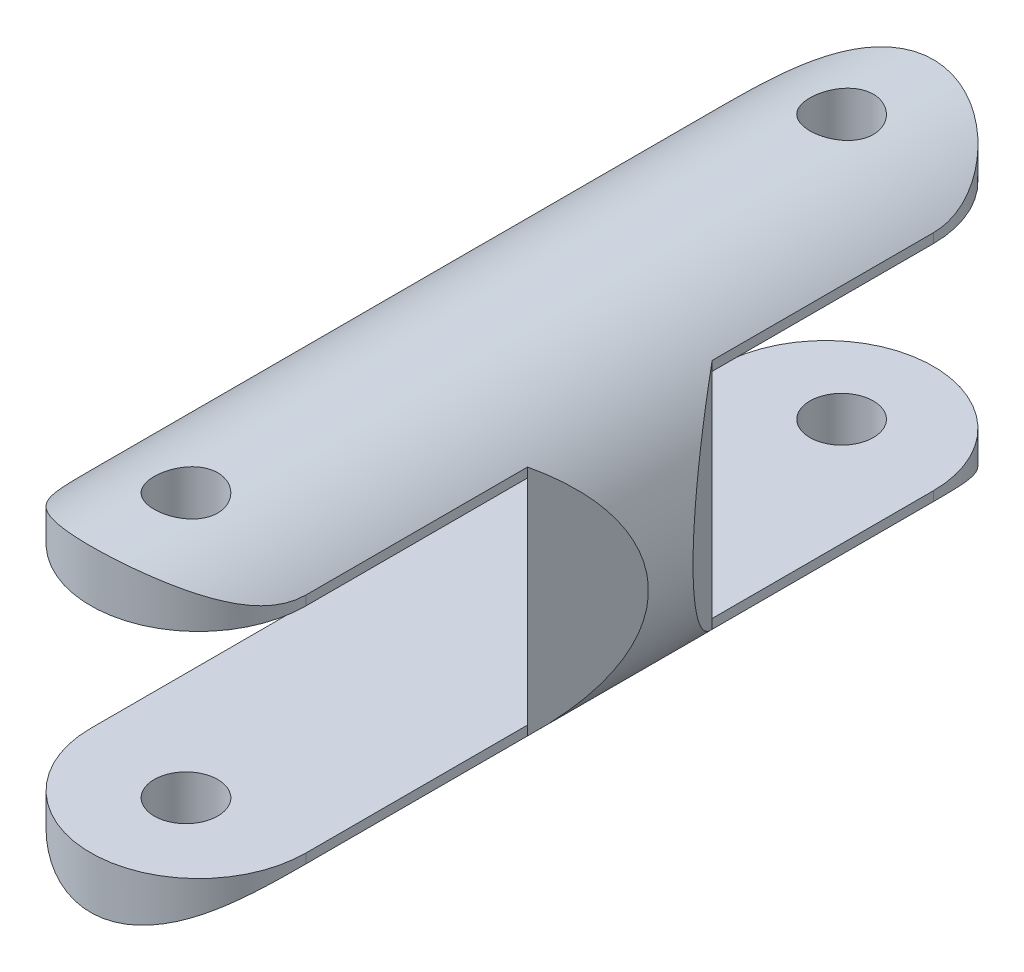
SolidWorks part; units mm, degrees
material "1060 Alloy"
ref_plane "Front Plane" through (0, 0, 0) normal (0, 0, 1) x (1, 0, 0)
ref_plane "Top Plane" through (0, 0, 0) normal (0, 1, 0) x (1, 0, 0)
ref_plane "Right Plane" through (0, 0, 0) normal (1, 0, 0) x (0, 0, -1)
sketch "Sketch1" plane through (0, 0, 0) normal (0, 0, 1) x (1, 0, 0)
  circle A0 centre (0, 0) radius 37.5
  dimension "D1" = 75
extrude "Boss-Extrude1" add sketch "Sketch1" along normal blind 200
sketch "Sketch3" plane through (0, 0, 0) normal (0, 1, 0) x (1, 0, 0)
  line L0 (0, -174.1224) -> (0, -25.9066) construction
  line L3 (0, -200) -> (0, 0) construction
  line L15 (-37.5, -200) -> (37.5, -200)
  line L18 (-37.5, 0) -> (37.5, 0)
  line L24 (0, -174.1224) -> (0, -25.9066) construction
  line L25 (-25.4742, -174.1224) -> (-25.4742, -121.8135)
  line L26 (25.4742, -174.1224) -> (25.4742, -121.8135)
  line L27 (-25.4742, -78.1865) -> (-37.5, -94.7274)
  line L28 (-37.5, 0) -> (-37.5, -200) construction
  line L29 (-37.5, -94.7274) -> (-37.5, 0)
  line L31 (25.4742, -78.1865) -> (37.5, -94.7274)
  line L32 (37.5, -94.7274) -> (37.5, 0)
  line L33 (-37.5, -100) -> (49962.5, -100) construction
  line L34 (37.5, -105.2726) -> (37.5, -200)
  line L35 (25.4742, -121.8135) -> (37.5, -105.2726)
  line L36 (-37.5, -105.2726) -> (-37.5, -200)
  line L37 (-25.4742, -121.8135) -> (-37.5, -105.2726)
  line L38 (-25.4742, -78.1865) -> (-25.4742, -25.9066)
  line L39 (25.4742, -78.1865) -> (25.4742, -25.9066)
  arc A2 (-25.4742, -174.1224) -> (25.4742, -174.1224) centre (0, -174.1224) ccw
  arc A3 (25.4742, -25.9066) -> (-25.4742, -25.9066) centre (0, -25.9066) ccw
  point P2 (0, -99.8889)
  point P3 (0, -100.0145)
  point P19 (-37.5, -100)
  point P32 (-37.5, -94.7281)
  point P33 (25.4519, -75.5415)
  point P34 (-25.4742, -121.8135)
extrude "Cut-Extrude1" cut sketch "Sketch3" against normal blind 99 and the other way blind 80
sketch "Sketch4" plane through (0, 0, 0) normal (0, 0, 1) x (1, 0, 0)
  line L0 (25.4742, 27.5194) -> (25.4742, -27.5194) construction
  line L1 (-25.4742, -25.283) -> (25.4742, -25.283)
  line L2 (-25.4742, -25.283) -> (-25.4742, 25.283)
  line L3 (-25.4742, 25.283) -> (25.4742, 25.283)
  line L4 (25.4742, -25.283) -> (25.4742, 25.283)
  line L5 (-25.4742, -25.283) -> (25.4742, 25.283) construction
  line L6 (-25.4742, 25.283) -> (25.4742, -25.283) construction
  point P0 (0, 0)
extrude "Cut-Extrude2" cut sketch "Sketch4" along normal blind 250
sketch "Sketch5" plane through (0, 0, 0) normal (0, 1, 0) x (1, 0, 0)
  circle A0 centre (0, -22.1174) radius 7.5
  circle A1 centre (0, -177.0687) radius 7.5
  dimension "D1" = 15
  dimension "D2" = 15
extrude "Cut-Extrude3" cut sketch "Sketch5" against normal blind 250 and the other way blind 250
